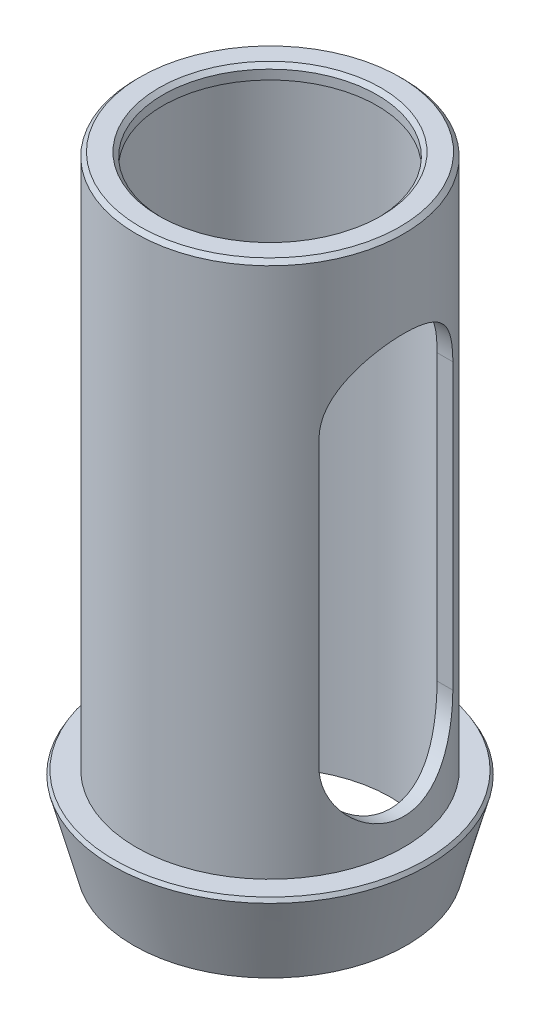
SolidWorks part; units mm, degrees
material "AISI 1020"
ref_plane "Front Plane" through (0, 0, 0) normal (0, 0, 1) x (1, 0, 0)
ref_plane "Top Plane" through (0, 0, 0) normal (0, 1, 0) x (1, 0, 0)
ref_plane "Right Plane" through (0, 0, 0) normal (1, 0, 0) x (0, 0, -1)
sketch "Sketch1" plane through (0, 0, 0) normal (0, 1, 0) x (1, 0, 0)
  circle A0 centre (0, 0) radius 25.908
  dimension "D1" = 51.816
extrude "Boss-Extrude1" add sketch "Sketch1" along normal blind 15.875 draft 15 draft outward yes
sketch "Sketch2" plane through (0, 15.875, 0) normal (0, 1, 0) x (1, 0, 0)
  circle A0 centre (0, 0) radius 25.4
  dimension "D1" = 50.8
extrude "Boss-Extrude2" add sketch "Sketch2" along normal blind 101.6
sketch "Sketch5" plane through (0, 0, 0) normal (0, -1, 0) x (1, 0, 0)
  circle A0 centre (0, 0) radius 22.86
  dimension "D1" = 45.72
extrude "Cut-Extrude2" cut sketch "Sketch5" against normal blind 114.935
sketch "Sketch6" plane through (0, 117.475, 0) normal (0, 1, 0) x (1, 0, 0)
  circle A0 centre (0, 0) radius 20.32
  dimension "D1" = 40.64
extrude "Cut-Extrude3" cut sketch "Sketch6" against normal blind 2.54
chamfer "Chamfer1" distance 0.762 angle 45 3 edges at (0, 15.875, 30.1617) (0, 117.475, 25.4) (0, 117.475, 20.32)
ref_plane "Plane1" through (25.4, 0, 0) normal (1, 0, 0) x (0, 0, -1)
sketch "Sketch7" plane through (25.4, 0, 0) normal (1, 0, 0) x (0, 0, -1)
  line L0 (-12.7, 87.63) -> (-12.7, 33.655)
  line L2 (12.7, 33.655) -> (12.7, 87.63)
  line L4 (29.5395, 15.875) -> (-29.5395, 15.875) construction
  line L5 (0, -12.4016) -> (0, 123.3523) construction
  arc A0 (-12.7, 87.63) -> (12.7, 87.63) centre (0, 87.63) cw
  arc A1 (-12.7, 33.655) -> (12.7, 33.655) centre (0, 33.655) ccw
  point P11 (0, 0)
  dimension "D1" = 12.7
  dimension "D2" = 53.975
  dimension "D3" = 17.78
extrude "Cut-Extrude6" cut sketch "Sketch7" against normal blind 7.62
